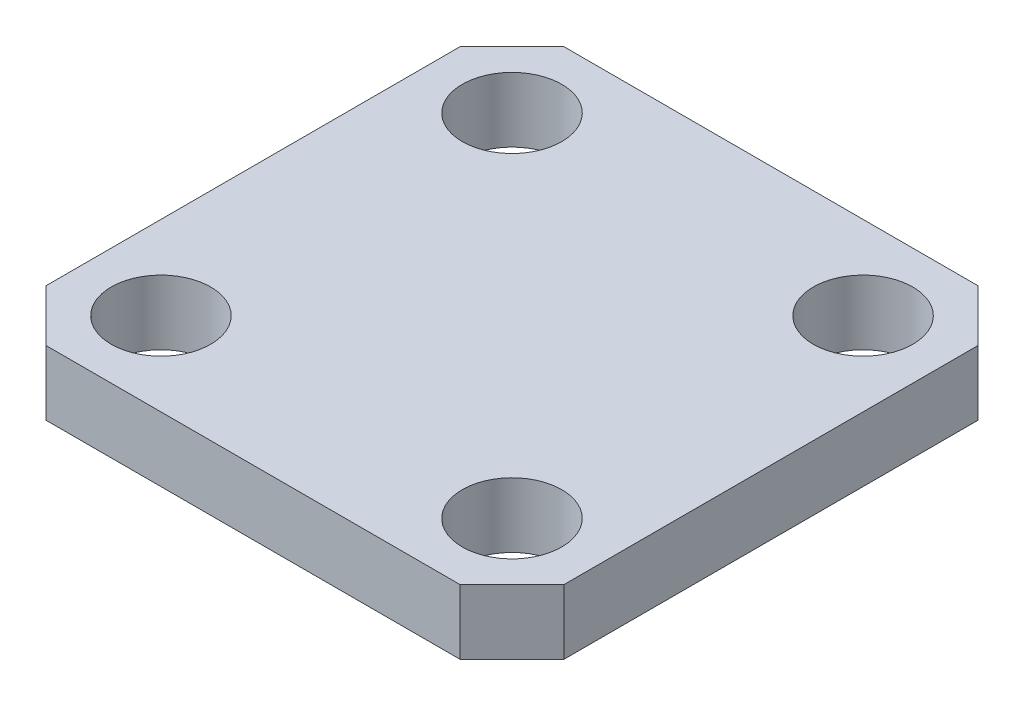
SolidWorks part; units mm, degrees
ref_plane "Front Plane" through (0, 0, 0) normal (0, 0, 1) x (1, 0, 0)
ref_plane "Top Plane" through (0, 0, 0) normal (0, 1, 0) x (1, 0, 0)
ref_plane "Right Plane" through (0, 0, 0) normal (1, 0, 0) x (0, 0, -1)
sketch "Sketch1" plane through (0, 0, 0) normal (0, 1, 0) x (1, 0, 0)
  line L1 (-6.35, 6.35) -> (6.35, 6.35)
  line L2 (-6.35, 6.35) -> (-6.35, -6.35)
  line L3 (-6.35, -6.35) -> (6.35, -6.35)
  line L4 (6.35, 6.35) -> (6.35, -6.35)
  line L5 (-6.35, 6.35) -> (6.35, -6.35) construction
  line L6 (-6.35, -6.35) -> (6.35, 6.35) construction
  point P0 (0, 0)
  dimension "D1" = 12.7
  dimension "D2" = 12.7
extrude "Boss-Extrude1" add sketch "Sketch1" along normal blind 1.5875
hole_wizard "#2 Clearance Hole1" positions "Sketch2" profile "Sketch3" hole size "#2" standard "ANSI Inch" end condition through all
sketch "Sketch2" plane through (0, 1.5875, 0) normal (0, 1, 0) x (1, 0, 0)
  line L0 (-4.3053, 4.3053) -> (4.3053, -4.3053)
  line L3 (4.3053, 4.3053) -> (-4.3053, -4.3053)
  point P0 (-4.3053, 4.3053)
  point P2 (4.3053, 4.3053)
  point P4 (4.3053, -4.3053)
  point P6 (-4.3053, -4.3053)
  point P20 (0, 0)
  dimension "D1" = 8.6106
  dimension "D2" = 8.6106
sketch "Sketch3" plane through (-4.3053, 1.5875, -4.3053) normal (1, 0, 0) x (0, 0, 1)
  line L0 (0, 0) -> (0, 1.5875)
  line L1 (0, 1.5875) -> (1.2192, 1.5875)
  line L2 (1.2192, 1.5875) -> (1.2192, 0)
  line L5 (1.2192, 0) -> (0, 0)
  line L11 (0, -6.35) -> (0, 107.95) construction
  dimension "Thru Hole Dia." = 2.4384
  dimension "Thru Hole Depth" = 1.5875
sketch "Sketch4" plane through (0, 1.5875, 0) normal (0, 1, 0) x (1, 0, 0)
  circle A0 centre (-4.3053, 4.3053) radius 2.0828
  dimension "D1" = 4.1656
chamfer "Chamfer1" distance 1.27 angle 45 4 edges at (-6.35, 0.7937, 6.35) (6.35, 0.7937, 6.35) (6.35, 0.7937, -6.35) (-6.35, 0.7937, -6.35)
